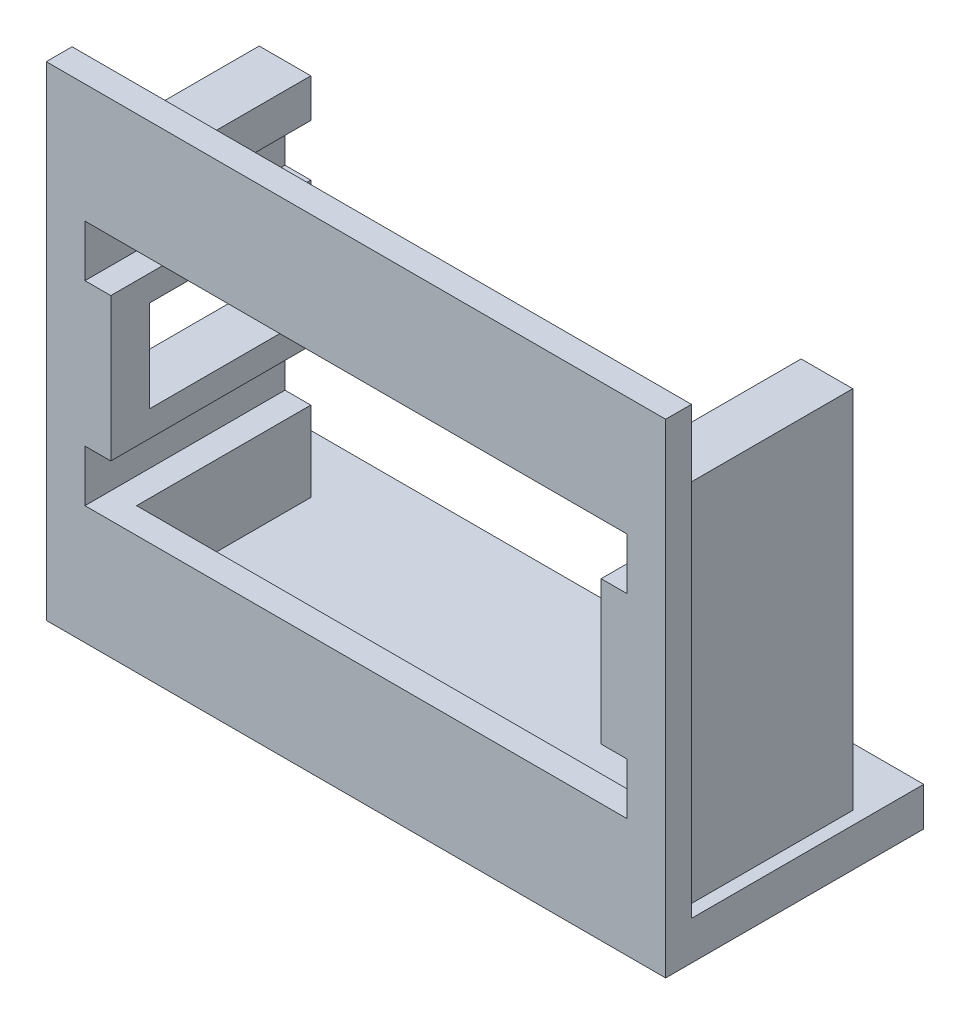
SolidWorks part; units mm, degrees
ref_plane "Front Plane" through (0, 0, 0) normal (0, 0, 1) x (1, 0, 0)
ref_plane "Top Plane" through (0, 0, 0) normal (0, 1, 0) x (1, 0, 0)
ref_plane "Right Plane" through (0, 0, 0) normal (1, 0, 0) x (0, 0, -1)
sketch "Sketch2" plane through (0, 0, 0) normal (0, 1, 0) x (1, 0, 0)
  line L1 (-100, 75) -> (100, 75)
  line L2 (-100, 75) -> (-100, -75)
  line L3 (-100, -75) -> (100, -75)
  line L4 (100, 75) -> (100, -75)
  line L5 (-100, 75) -> (100, -75) construction
  line L6 (-100, -75) -> (100, 75) construction
  point P0 (0, 0)
  dimension "D1" = 200
  dimension "D2" = 150
extrude "Boss-Extrude1" add sketch "Sketch2" along normal blind 80
fillet "Fillet1" radius 10 4 edges at (-100, 40, -75) (100, 40, -75) (100, 40, 75) (-100, 40, 75)
shell "Shell1" thickness 2
sketch "Sketch5" plane through (0, 0, 75) normal (0, 0, 1) x (1, 0, 0)
  line L1 (-18.25, 44.5) -> (18.25, 44.5)
  line L2 (-18.25, 44.5) -> (-18.25, 17)
  line L3 (-18.25, 17) -> (18.25, 17)
  line L4 (18.25, 44.5) -> (18.25, 17)
  line L5 (-18.25, 43.5) -> (-19.75, 44.366)
  line L6 (-19.75, 44.366) -> (-19.75, 41.634)
  line L7 (-19.75, 41.634) -> (-18.25, 42.5)
  line L8 (-18.25, 42.5) -> (-18.25, 43.5)
  line L9 (0, 44.5) -> (0, 17) construction
  line L10 (-18.25, 30.75) -> (18.25, 30.75) construction
  line L11 (-19.75, 19.866) -> (-18.25, 19)
  line L12 (-19.75, 17.134) -> (-19.75, 19.866)
  line L13 (-18.25, 18) -> (-19.75, 17.134)
  line L14 (-18.25, 19) -> (-18.25, 18)
  line L15 (19.75, 17.134) -> (19.75, 19.866)
  line L16 (18.25, 18) -> (19.75, 17.134)
  line L17 (18.25, 19) -> (18.25, 18)
  line L18 (19.75, 19.866) -> (18.25, 19)
  line L19 (19.75, 41.634) -> (18.25, 42.5)
  line L20 (19.75, 44.366) -> (19.75, 41.634)
  line L21 (18.25, 43.5) -> (19.75, 44.366)
  line L22 (18.25, 42.5) -> (18.25, 43.5)
  line L23 (-90, 15) -> (90, 15) construction
  point P4 (0, 17)
  dimension "D1" = 36.5
  dimension "D2" = 27.5
  dimension "D3" = 60
  dimension "D4" = 60
  dimension "D5" = 1
  dimension "D6" = 1
  dimension "D7" = 1.5
  dimension "D8" = 2
extrude "Cut-Extrude1" cut sketch "Sketch5" against normal up to surface (2 mm away) contours L1 L4 L3 L2 | L7 L8 L5 L6 | L12 L11 L14 L13 | L20 L19 L22 L21 | L15 L18 L17 L16 up to face at (0, 47.5, 73)
sketch "Sketch6" plane through (0, 0, 73) normal (0, 0, -1) x (-1, 0, 0)
  line L0 (18.25, 15) -> (21.25, 15)
  line L2 (-21.25, 47.5) -> (-21.25, 15)
  line L4 (19.75, 44.366) -> (18.25, 43.5)
  line L5 (19.75, 41.634) -> (19.75, 44.366)
  line L6 (18.25, 42.5) -> (19.75, 41.634)
  line L7 (18.25, 43.5) -> (18.25, 42.5)
  line L8 (19.75, 44.366) -> (18.25, 43.5)
  line L9 (19.75, 41.634) -> (19.75, 44.366)
  line L10 (18.25, 42.5) -> (19.75, 41.634)
  line L12 (18.25, 44.5) -> (-18.25, 44.5)
  line L13 (-18.25, 44.5) -> (-18.25, 17)
  line L14 (-18.25, 17) -> (18.25, 17)
  line L15 (18.25, 17) -> (18.25, 44.5)
  line L17 (-18.25, 47.5) -> (-18.25, 43.5)
  line L19 (18.25, 15) -> (18.25, 18)
  line L20 (-19.75, 41.634) -> (-18.25, 42.5)
  line L21 (-18.25, 42.5) -> (-18.25, 43.5)
  line L22 (-18.25, 43.5) -> (-19.75, 44.366)
  line L23 (-19.75, 44.366) -> (-19.75, 41.634)
  line L24 (-19.75, 41.634) -> (-18.25, 42.5)
  line L26 (-18.25, 43.5) -> (-19.75, 44.366)
  line L27 (-19.75, 44.366) -> (-19.75, 41.634)
  line L28 (-19.75, 19.866) -> (-19.75, 17.134)
  line L29 (-18.25, 19) -> (-19.75, 19.866)
  line L30 (-18.25, 18) -> (-18.25, 19)
  line L31 (-19.75, 17.134) -> (-18.25, 18)
  line L32 (-19.75, 19.866) -> (-19.75, 17.134)
  line L33 (-18.25, 19) -> (-19.75, 19.866)
  line L35 (-19.75, 17.134) -> (-18.25, 18)
  line L36 (19.75, 19.866) -> (18.25, 19)
  line L37 (18.25, 19) -> (18.25, 18)
  line L38 (18.25, 18) -> (19.75, 17.134)
  line L39 (19.75, 17.134) -> (19.75, 19.866)
  line L40 (19.75, 19.866) -> (18.25, 19)
  line L42 (18.25, 18) -> (19.75, 17.134)
  line L43 (19.75, 17.134) -> (19.75, 19.866)
  line L44 (21.25, 47.5) -> (21.25, 15)
  line L45 (-18.25, 15) -> (-21.25, 15)
  line L46 (-18.25, 42.5) -> (-18.25, 19)
  line L47 (18.25, 43.5) -> (18.25, 47.5)
  line L48 (18.25, 19) -> (18.25, 42.5)
  line L49 (-18.25, 18) -> (-18.25, 15)
  line L50 (21.25, 47.5) -> (18.25, 47.5)
  line L51 (-21.25, 47.5) -> (-18.25, 47.5)
  line L54 (18.25, 44.5) -> (-18.25, 44.5) construction
  line L55 (90, 15) -> (-90, 15) construction
  dimension "D6" = 3
  dimension "D7" = 3
  dimension "D8" = 3
  dimension "D1" = 0
  dimension "D2" = 0
  dimension "D3" = 0
  dimension "D4" = 0
  dimension "D5" = 0
extrude "Boss-Extrude2" add sketch "Sketch6" along normal blind 16
sketch "Sketch7" plane through (100, 0, 0) normal (1, 0, 0) x (0, 0, -1)
  line L0 (-65, 15) -> (65, 15) construction
  line L1 (-18.25, 44.5) -> (18.25, 44.5)
  line L2 (-18.25, 44.5) -> (-18.25, 17)
  line L3 (-18.25, 17) -> (18.25, 17)
  line L4 (18.25, 44.5) -> (18.25, 17)
  line L5 (-18.25, 43.5) -> (-19.75, 44.366)
  line L6 (-19.75, 44.366) -> (-19.75, 41.634)
  line L7 (-19.75, 41.634) -> (-18.25, 42.5)
  line L8 (-18.25, 42.5) -> (-18.25, 43.5)
  line L9 (0, 44.5) -> (0, 17) construction
  line L10 (-18.25, 30.75) -> (18.25, 30.75) construction
  line L11 (-19.75, 19.866) -> (-18.25, 19)
  line L12 (-19.75, 17.134) -> (-19.75, 19.866)
  line L13 (-18.25, 18) -> (-19.75, 17.134)
  line L14 (-18.25, 19) -> (-18.25, 18)
  line L15 (19.75, 17.134) -> (19.75, 19.866)
  line L16 (18.25, 18) -> (19.75, 17.134)
  line L17 (18.25, 19) -> (18.25, 18)
  line L18 (19.75, 19.866) -> (18.25, 19)
  line L19 (19.75, 41.634) -> (18.25, 42.5)
  line L20 (19.75, 44.366) -> (19.75, 41.634)
  line L21 (18.25, 43.5) -> (19.75, 44.366)
  line L22 (18.25, 42.5) -> (18.25, 43.5)
  dimension "D1" = 36.5
  dimension "D2" = 27.5
  dimension "D3" = 60
  dimension "D4" = 60
  dimension "D5" = 1
  dimension "D6" = 1
  dimension "D7" = 1.5
  dimension "D8" = 2
extrude "Cut-Extrude2" cut sketch "Sketch7" against normal blind 2 contours L1 L4 L3 L2 | L7 L8 L5 L6 | L12 L11 L14 L13 | L20 L19 L22 L21 | L15 L18 L17 L16
sketch "Sketch8" plane through (98, 0, 0) normal (-1, 0, 0) x (0, 0, 1)
  line L0 (65, 15) -> (-65, 15) construction
  line L1 (-21.25, 47.5) -> (-18.25, 47.5)
  line L2 (-21.25, 47.5) -> (-21.25, 15)
  line L3 (-21.25, 15) -> (-18.25, 15)
  line L4 (19.75, 44.366) -> (18.25, 43.5)
  line L5 (19.75, 41.634) -> (19.75, 44.366)
  line L6 (18.25, 42.5) -> (19.75, 41.634)
  line L7 (18.25, 43.5) -> (18.25, 42.5)
  line L8 (19.75, 44.366) -> (18.25, 43.5)
  line L9 (19.75, 41.634) -> (19.75, 44.366)
  line L10 (18.25, 42.5) -> (19.75, 41.634)
  line L20 (-19.75, 41.634) -> (-18.25, 42.5)
  line L21 (-18.25, 42.5) -> (-18.25, 43.5)
  line L22 (-18.25, 43.5) -> (-19.75, 44.366)
  line L23 (-19.75, 44.366) -> (-19.75, 41.634)
  line L24 (-19.75, 41.634) -> (-18.25, 42.5)
  line L26 (-18.25, 43.5) -> (-19.75, 44.366)
  line L27 (-19.75, 44.366) -> (-19.75, 41.634)
  line L28 (-19.75, 19.866) -> (-19.75, 17.134)
  line L29 (-18.25, 19) -> (-19.75, 19.866)
  line L30 (-18.25, 18) -> (-18.25, 19)
  line L31 (-19.75, 17.134) -> (-18.25, 18)
  line L32 (-19.75, 19.866) -> (-19.75, 17.134)
  line L33 (-18.25, 19) -> (-19.75, 19.866)
  line L35 (-19.75, 17.134) -> (-18.25, 18)
  line L36 (19.75, 19.866) -> (18.25, 19)
  line L37 (18.25, 19) -> (18.25, 18)
  line L38 (18.25, 18) -> (19.75, 17.134)
  line L39 (19.75, 17.134) -> (19.75, 19.866)
  line L40 (19.75, 19.866) -> (18.25, 19)
  line L42 (18.25, 18) -> (19.75, 17.134)
  line L43 (19.75, 17.134) -> (19.75, 19.866)
  line L44 (-18.25, 47.5) -> (-18.25, 43.5)
  line L46 (-18.25, 42.5) -> (-18.25, 19) construction
  line L47 (18.25, 44.5) -> (-18.25, 44.5) construction
  line L48 (-18.25, 42.5) -> (-18.25, 19)
  line L49 (-18.25, 18) -> (-18.25, 15)
  line L50 (18.25, 42.5) -> (18.25, 19) construction
  line L51 (18.25, 47.5) -> (21.25, 47.5)
  line L52 (18.25, 47.5) -> (18.25, 43.5)
  line L53 (18.25, 15) -> (21.25, 15)
  line L54 (21.25, 47.5) -> (21.25, 15)
  line L55 (18.25, 42.5) -> (18.25, 19)
  line L56 (18.25, 18) -> (18.25, 15)
  dimension "D6" = 3
  dimension "D7" = 3
  dimension "D2" = 3
  dimension "D1" = 0
  dimension "D3" = 0
  dimension "D4" = 0
  dimension "D5" = 0
extrude "Boss-Extrude3" add sketch "Sketch8" along normal blind 16
sketch "Sketch10" plane through (-100, 0, 0) normal (-1, 0, 0) x (0, 0, 1)
  line L1 (-18.25, 44.5) -> (18.25, 44.5)
  line L2 (-18.25, 44.5) -> (-18.25, 17)
  line L3 (-18.25, 17) -> (18.25, 17)
  line L4 (18.25, 44.5) -> (18.25, 17)
  line L5 (-18.25, 43.5) -> (-19.75, 44.366)
  line L6 (-19.75, 44.366) -> (-19.75, 41.634)
  line L7 (-19.75, 41.634) -> (-18.25, 42.5)
  line L8 (-18.25, 42.5) -> (-18.25, 43.5)
  line L9 (0, 44.5) -> (0, 17) construction
  line L10 (-18.25, 30.75) -> (18.25, 30.75) construction
  line L11 (-19.75, 19.866) -> (-18.25, 19)
  line L12 (-19.75, 17.134) -> (-19.75, 19.866)
  line L13 (-18.25, 18) -> (-19.75, 17.134)
  line L14 (-18.25, 19) -> (-18.25, 18)
  line L15 (19.75, 17.134) -> (19.75, 19.866)
  line L16 (18.25, 18) -> (19.75, 17.134)
  line L17 (18.25, 19) -> (18.25, 18)
  line L18 (19.75, 19.866) -> (18.25, 19)
  line L19 (19.75, 41.634) -> (18.25, 42.5)
  line L20 (19.75, 44.366) -> (19.75, 41.634)
  line L21 (18.25, 43.5) -> (19.75, 44.366)
  line L22 (18.25, 42.5) -> (18.25, 43.5)
  line L23 (-65, 15) -> (65, 15) construction
  dimension "D1" = 36.5
  dimension "D2" = 27.5
  dimension "D3" = 60
  dimension "D4" = 60
  dimension "D5" = 1
  dimension "D6" = 1
  dimension "D7" = 1.5
  dimension "D8" = 2
extrude "Cut-Extrude4" cut sketch "Sketch10" against normal blind 2 contours L1 L4 L3 L2 | L7 L8 L5 L6 | L12 L11 L14 L13 | L20 L19 L22 L21 | L15 L18 L17 L16
sketch "Sketch11" plane through (-98, 0, 0) normal (1, 0, 0) x (0, 0, -1)
  line L1 (-18.25, 42.5) -> (-18.25, 19) construction
  line L2 (-18.25, 47.5) -> (-21.25, 47.5)
  line L3 (-18.25, 47.5) -> (-18.25, 43.5)
  line L4 (19.75, 44.366) -> (18.25, 43.5)
  line L5 (19.75, 41.634) -> (19.75, 44.366)
  line L6 (18.25, 42.5) -> (19.75, 41.634)
  line L7 (18.25, 43.5) -> (18.25, 42.5)
  line L8 (19.75, 44.366) -> (18.25, 43.5)
  line L9 (19.75, 41.634) -> (19.75, 44.366)
  line L10 (18.25, 42.5) -> (19.75, 41.634)
  line L20 (-19.75, 41.634) -> (-18.25, 42.5)
  line L21 (-18.25, 42.5) -> (-18.25, 43.5)
  line L22 (-18.25, 43.5) -> (-19.75, 44.366)
  line L23 (-19.75, 44.366) -> (-19.75, 41.634)
  line L24 (-19.75, 41.634) -> (-18.25, 42.5)
  line L26 (-18.25, 43.5) -> (-19.75, 44.366)
  line L27 (-19.75, 44.366) -> (-19.75, 41.634)
  line L28 (-19.75, 19.866) -> (-19.75, 17.134)
  line L29 (-18.25, 19) -> (-19.75, 19.866)
  line L30 (-18.25, 18) -> (-18.25, 19)
  line L31 (-19.75, 17.134) -> (-18.25, 18)
  line L32 (-19.75, 19.866) -> (-19.75, 17.134)
  line L33 (-18.25, 19) -> (-19.75, 19.866)
  line L35 (-19.75, 17.134) -> (-18.25, 18)
  line L36 (19.75, 19.866) -> (18.25, 19)
  line L37 (18.25, 19) -> (18.25, 18)
  line L38 (18.25, 18) -> (19.75, 17.134)
  line L39 (19.75, 17.134) -> (19.75, 19.866)
  line L40 (19.75, 19.866) -> (18.25, 19)
  line L42 (18.25, 18) -> (19.75, 17.134)
  line L43 (19.75, 17.134) -> (19.75, 19.866)
  line L44 (-18.25, 15) -> (-21.25, 15)
  line L45 (-21.25, 47.5) -> (-21.25, 15)
  line L46 (65, 15) -> (-65, 15) construction
  line L47 (18.25, 44.5) -> (-18.25, 44.5) construction
  line L48 (-18.25, 42.5) -> (-18.25, 19)
  line L49 (-18.25, 18) -> (-18.25, 15)
  line L50 (18.25, 42.5) -> (18.25, 19) construction
  line L51 (18.25, 47.5) -> (21.25, 47.5)
  line L52 (18.25, 47.5) -> (18.25, 43.5)
  line L53 (18.25, 15) -> (21.25, 15)
  line L54 (21.25, 47.5) -> (21.25, 15)
  line L55 (18.25, 42.5) -> (18.25, 19)
  line L56 (18.25, 18) -> (18.25, 15)
  dimension "D2" = 3
  dimension "D6" = 3
  dimension "D7" = 3
  dimension "D1" = 0
  dimension "D3" = 0
  dimension "D4" = 0
  dimension "D5" = 0
extrude "Boss-Extrude4" add sketch "Sketch11" along normal blind 16
sketch "Sketch13" plane through (0, 0, 75) normal (0, 0, 1) x (1, 0, 0)
  line L0 (-18.25, 30.75) -> (18.25, 30.75) construction
  line L1 (-18.25, 30.75) -> (18.25, 30.75) construction
  line L2 (41, 40.3) -> (39, 40.3)
  line L3 (41, 40.3) -> (79, 40.3)
  line L4 (41, 40.3) -> (41, 21.2)
  line L5 (41, 21.2) -> (79, 21.2)
  line L6 (79, 40.3) -> (79, 21.2)
  line L7 (39, 40.3) -> (39, 36.3)
  line L8 (39, 36.3) -> (41, 36.3)
  line L9 (41, 40.3) -> (41, 36.3)
  line L10 (60, 40.3) -> (60, 21.2) construction
  line L11 (41, 21.2) -> (39, 21.2)
  line L12 (39, 21.2) -> (39, 25.2)
  line L13 (39, 25.2) -> (41, 25.2)
  line L14 (41, 21.2) -> (41, 25.2)
  line L15 (79, 21.2) -> (79, 25.2)
  line L16 (81, 25.2) -> (79, 25.2)
  line L17 (81, 21.2) -> (81, 25.2)
  line L18 (79, 21.2) -> (81, 21.2)
  line L19 (79, 40.3) -> (81, 40.3)
  line L20 (81, 40.3) -> (81, 36.3)
  line L21 (81, 36.3) -> (79, 36.3)
  line L22 (79, 40.3) -> (79, 36.3)
  point P6 (41, 30.75)
  point P7 (60, 21.2)
  dimension "D1" = 19.1
  dimension "D2" = 38
  dimension "D3" = 60
  dimension "D4" = 4
  dimension "D8" = 2
extrude "Cut-Extrude5" cut sketch "Sketch13" against normal up to surface (2 mm away) contours L3 L6 L5 L4 | L7 L8 L9 L2 | L12 L13 L14 L11 | L17 L16 L15 L18 | L20 L21 L22 L19 up to face at (0, 41.5833, 73)
sketch "Sketch14" plane through (0, 0, 73) normal (0, 0, -1) x (-1, 0, 0)
  line L0 (-21.25, 15) -> (-90, 15) construction
  line L1 (-79, 43.3) -> (-83, 43.3)
  line L2 (-79, 43.3) -> (-79, 40.3)
  line L3 (-79, 15) -> (-83, 15)
  line L6 (-83, 43.3) -> (-83, 15)
  line L12 (-39, 40.3) -> (-41, 40.3)
  line L13 (-39, 36.3) -> (-39, 40.3)
  line L14 (-41, 36.3) -> (-39, 36.3)
  line L15 (-41, 40.3) -> (-41, 36.3)
  line L16 (-39, 40.3) -> (-41, 40.3)
  line L17 (-39, 36.3) -> (-39, 40.3)
  line L18 (-41, 36.3) -> (-39, 36.3)
  line L20 (-79, 40.3) -> (-81, 40.3)
  line L21 (-81, 40.3) -> (-81, 36.3)
  line L22 (-81, 36.3) -> (-79, 36.3)
  line L23 (-79, 36.3) -> (-79, 40.3)
  line L24 (-79, 40.3) -> (-81, 40.3)
  line L25 (-81, 40.3) -> (-81, 36.3)
  line L26 (-81, 36.3) -> (-79, 36.3)
  line L28 (-79, 21.2) -> (-79, 25.2)
  line L29 (-79, 25.2) -> (-81, 25.2)
  line L30 (-81, 25.2) -> (-81, 21.2)
  line L31 (-81, 21.2) -> (-79, 21.2)
  line L33 (-79, 25.2) -> (-81, 25.2)
  line L34 (-81, 25.2) -> (-81, 21.2)
  line L35 (-81, 21.2) -> (-79, 21.2)
  line L36 (-39, 21.2) -> (-39, 25.2)
  line L37 (-39, 25.2) -> (-41, 25.2)
  line L38 (-41, 25.2) -> (-41, 21.2)
  line L39 (-41, 21.2) -> (-39, 21.2)
  line L40 (-39, 21.2) -> (-39, 25.2)
  line L41 (-39, 25.2) -> (-41, 25.2)
  line L43 (-41, 21.2) -> (-39, 21.2)
  line L44 (-39, 40.3) -> (-81, 40.3) construction
  line L45 (-41, 43.3) -> (-37, 43.3)
  line L46 (-41, 43.3) -> (-41, 40.3)
  line L47 (-41, 15) -> (-37, 15)
  line L48 (-37, 43.3) -> (-37, 15)
  line L49 (-79, 36.3) -> (-79, 25.2) construction
  line L50 (-41, 36.3) -> (-41, 25.2) construction
  line L51 (-79, 36.3) -> (-79, 25.2)
  line L52 (-79, 21.2) -> (-79, 15)
  line L53 (-41, 36.3) -> (-41, 25.2)
  line L54 (-41, 21.2) -> (-41, 15)
  dimension "D1" = 3
  dimension "D6" = 4
  dimension "D7" = 4
  dimension "D2" = 0
  dimension "D3" = 0
  dimension "D4" = 0
  dimension "D5" = 0
extrude "Boss-Extrude5" add sketch "Sketch14" along normal blind 13.5
sketch "Sketch15" plane through (37, 0, 0) normal (-1, 0, 0) x (0, 0, 1)
  line L4 (59.5, 15) -> (59.5, 43.3) construction
  line L5 (73, 15) -> (73, 43.3) construction
  line L6 (59.5, 43.3) -> (59.5, 15) construction
  line L7 (59.5, 36.3) -> (75, 36.3) construction
  line L8 (59.5, 25.2) -> (75, 25.2) construction
  line L12 (72, 27.2) -> (72, 34.3)
  line L13 (72, 34.3) -> (61.5, 34.3)
  line L14 (61.5, 34.3) -> (61.5, 27.2)
  line L15 (61.5, 27.2) -> (72, 27.2)
  dimension "D1" = 2
  dimension "D2" = 1
  dimension "D3" = 2
  dimension "D4" = 2
extrude "Cut-Extrude6" cut sketch "Sketch15" against normal up to surface (4 mm away) up to face at (41, 30.75, 67.25)
sketch "Sketch18" plane through (0, 0, 0) normal (1, 0, 0) x (0, 0, -1)
  line L0 (0, 0) -> (0, 10) construction
  line L3 (-42.5, 0) -> (-70, 0)
  line L4 (-70, 0) -> (-47.5, 10)
  line L5 (-47.5, 10) -> (-42.5, 10)
  line L6 (-42.5, 10) -> (-42.5, 0)
  line L7 (65, 0) -> (-65, 0) construction
  dimension "D1" = 10
  dimension "D2" = 70
  dimension "D3" = 5
  dimension "D4" = 42.5
revolve "Cut-Revolve1" cut sketch "Sketch18" angle 360 about L0
sketch "Sketch20" plane through (0, 0, 0) normal (0, -1, 0) x (1, 0, 0)
  circle A0 centre (0, -42.5) radius 8
  circle A1 centre (0, 0) radius 42.5 construction
  circle A2 centre (0, 0) radius 42.5 construction
  dimension "D1" = 16
extrude "Cut-Extrude8" cut sketch "Sketch20" against normal up to surface (15 mm away) up to face at (12, 15, 26.25)
sketch "Sketch21" plane through (0, 0, 75) normal (0, 0, 1) x (1, 0, 0)
  line L0 (39, 21.2) -> (81, 21.2) construction
  line L1 (36, 49.5) -> (84, 49.5)
  line L2 (36, 49.5) -> (36, 12)
  line L3 (36, 12) -> (84, 12)
  line L4 (84, 49.5) -> (84, 12)
  line L5 (36, 49.5) -> (84, 12) construction
  line L6 (36, 12) -> (84, 49.5) construction
  line L7 (39, 21.2) -> (81, 21.2) construction
  line L8 (41, 36.3) -> (41, 25.2) construction
  line L9 (41, 36.3) -> (41, 25.2) construction
  line L10 (79, 36.3) -> (79, 25.2) construction
  line L11 (41, 15) -> (79, 15) construction
  point P0 (60, 30.75)
  point P10 (60, 21.2)
  point P12 (41, 30.75)
  dimension "D1" = 5
  dimension "D2" = 3
split "Split1" trim tools "Sketch21" bodies to split 113 resulting bodies 114 115
sketch "Sketch22" plane through (0, 15, 0) normal (0, 1, 0) x (1, 0, 0)
  line L0 (36, -75) -> (84, -75) construction
  line L1 (36, -75) -> (84, -75)
  line L2 (36, -75) -> (36, -55)
  line L3 (36, -55) -> (84, -55)
  line L4 (84, -75) -> (84, -55)
  line L5 (84, -73) -> (84, -21.25) construction
  line L6 (36, 73) -> (36, -73) construction
  dimension "D1" = 20
split "Split2" trim tools "Sketch22" bodies to split 114 resulting bodies 116 117
delete or keep bodies "Body-Delete/Keep 1" type delete bodies bodies 116 115
